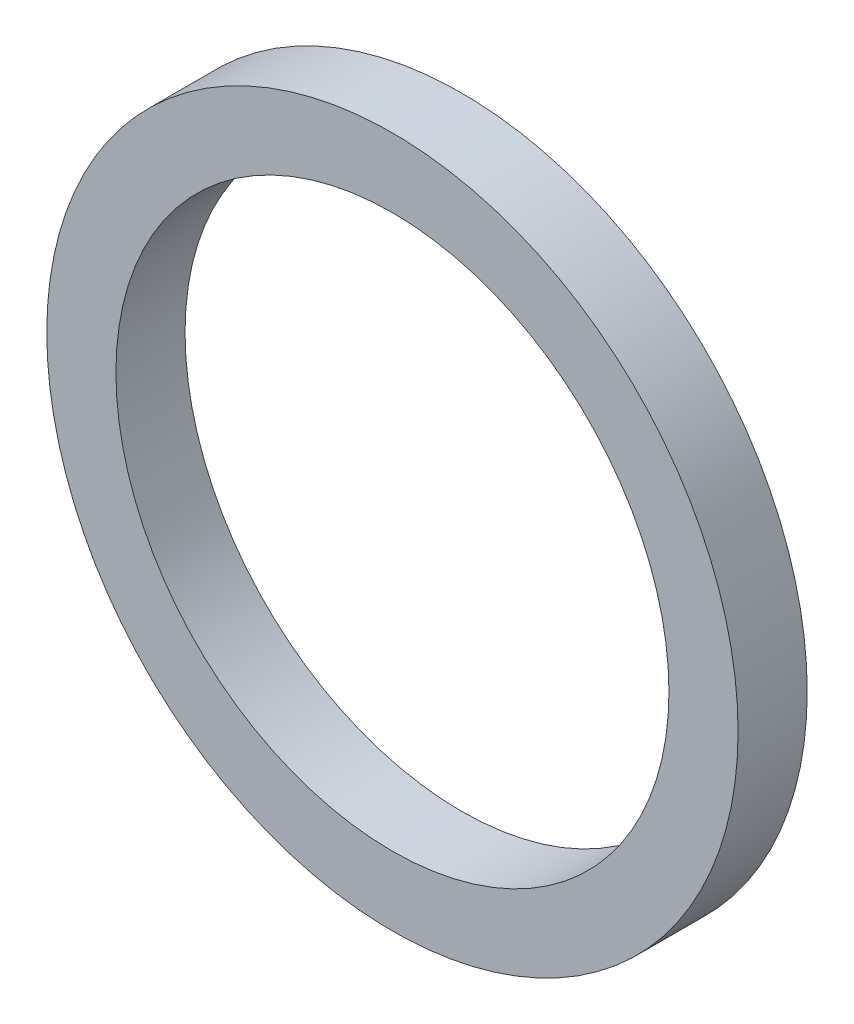
SolidWorks part; units mm, degrees
ref_plane "前视基准面" through (0, 0, 0) normal (0, 0, 1) x (1, 0, 0)
ref_plane "上视基准面" through (0, 0, 0) normal (0, 1, 0) x (1, 0, 0)
ref_plane "右视基准面" through (0, 0, 0) normal (1, 0, 0) x (0, 0, -1)
sketch "草图1" plane through (0, 0, 0) normal (0, 0, 1) x (1, 0, 0)
  circle A0 centre (0, 0) radius 4
  circle A1 centre (0, 0) radius 5
extrude "凸台-拉伸1" add sketch "草图1" along normal blind 1
